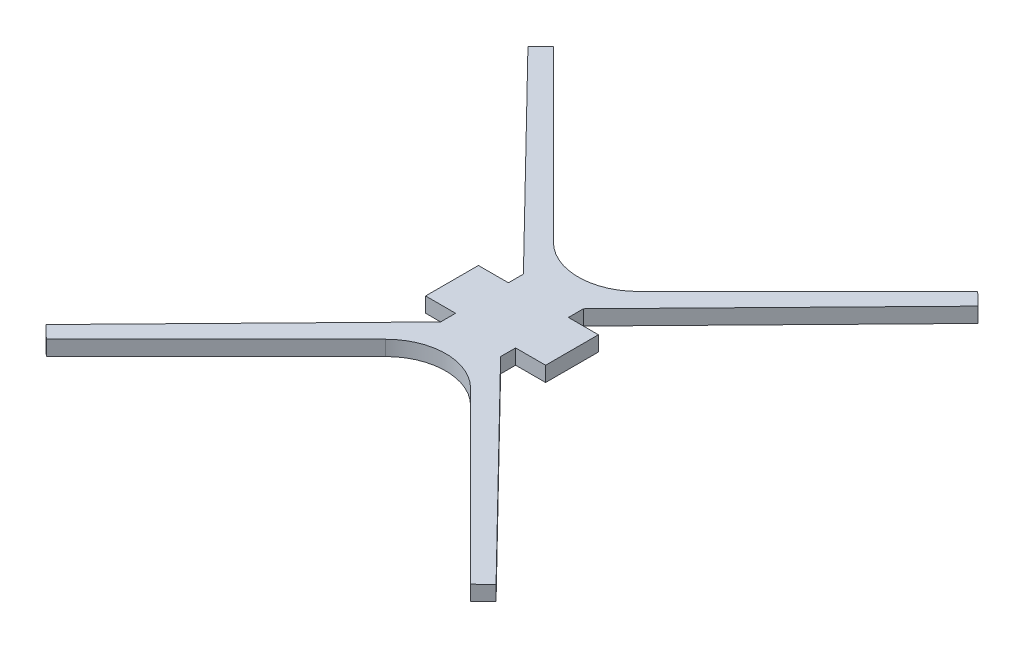
SolidWorks part; units mm, degrees
material "Acrylic (Medium-high impact)"
ref_plane "Front Plane" through (0, 0, 0) normal (0, 0, 1) x (1, 0, 0)
ref_plane "Top Plane" through (0, 0, 0) normal (0, 1, 0) x (1, 0, 0)
ref_plane "Right Plane" through (0, 0, 0) normal (1, 0, 0) x (0, 0, -1)
sketch "Sketch1" plane through (0, 0, 0) normal (0, 1, 0) x (1, 0, 0)
  line L0 (12.7, 11.176) -> (12.7, 0) construction
  line L1 (0, 0) -> (25.4, 0)
  line L2 (0, 0) -> (0, 11.176)
  line L3 (0, 11.176) -> (25.4, 11.176)
  line L4 (25.4, 0) -> (25.4, 11.176)
  line L5 (19.05, 11.176) -> (19.05, 14.351)
  line L6 (19.05, 11.176) -> (6.35, 11.176)
  line L7 (12.7, 11.176) -> (12.7, 14.351)
  line L8 (19.05, 14.351) -> (6.35, 14.351)
  line L9 (6.35, 11.176) -> (6.35, 14.351)
  line L10 (0, 5.588) -> (25.4, 5.588) construction
  line L11 (19.05, 0) -> (19.05, -3.175)
  line L12 (19.05, 0) -> (6.35, 0)
  line L13 (6.35, 0) -> (6.35, -3.175)
  line L14 (19.05, -3.175) -> (6.35, -3.175)
  line L15 (3.7197, 23.3313) -> (-32.2013, 59.2523)
  line L16 (6.35, 14.351) -> (-34.9262, 56.5894)
  line L17 (-34.9262, 56.5894) -> (-32.2013, 59.2523)
  line L18 (60.3262, 56.5894) -> (57.6013, 59.2523)
  line L19 (19.05, 14.351) -> (60.3262, 56.5894)
  line L20 (21.6803, 23.3313) -> (57.6013, 59.2523)
  line L21 (6.35, -3.175) -> (-34.9262, -45.4134)
  line L22 (3.7197, -12.1553) -> (-32.2013, -48.0763)
  line L23 (21.6803, -12.1553) -> (57.6013, -48.0763)
  line L24 (19.05, -3.175) -> (60.3262, -45.4134)
  line L25 (60.3262, -45.4134) -> (57.6013, -48.0763)
  line L26 (-34.9262, -45.4134) -> (-32.2013, -48.0763)
  arc A0 (17.1901, -7.6651) -> (8.2099, -7.6651) centre (12.7, -12.1553) ccw
  arc A1 (17.1901, 18.8411) -> (8.2099, 18.8411) centre (12.7, 23.3313) cw
  arc A2 (21.6803, -12.1553) -> (3.7197, -12.1553) centre (12.7, -21.1355) ccw
  arc A3 (21.6803, 23.3313) -> (3.7197, 23.3313) centre (12.7, 32.3115) cw
  point P29 (12.7, -3.175)
  point P40 (12.7, -3.175)
  dimension "D8" = 6.35
  dimension "D9" = 12.7
  dimension "D1" = 11.176
  dimension "D2" = 25.4
  dimension "D3" = 3.175
  dimension "D4" = 6.35
  dimension "D5" = 45
  dimension "D6" = 3.81
  dimension "D7" = 63.5
extrude "Boss-Extrude1" add sketch "Sketch1" along normal blind 3.175
